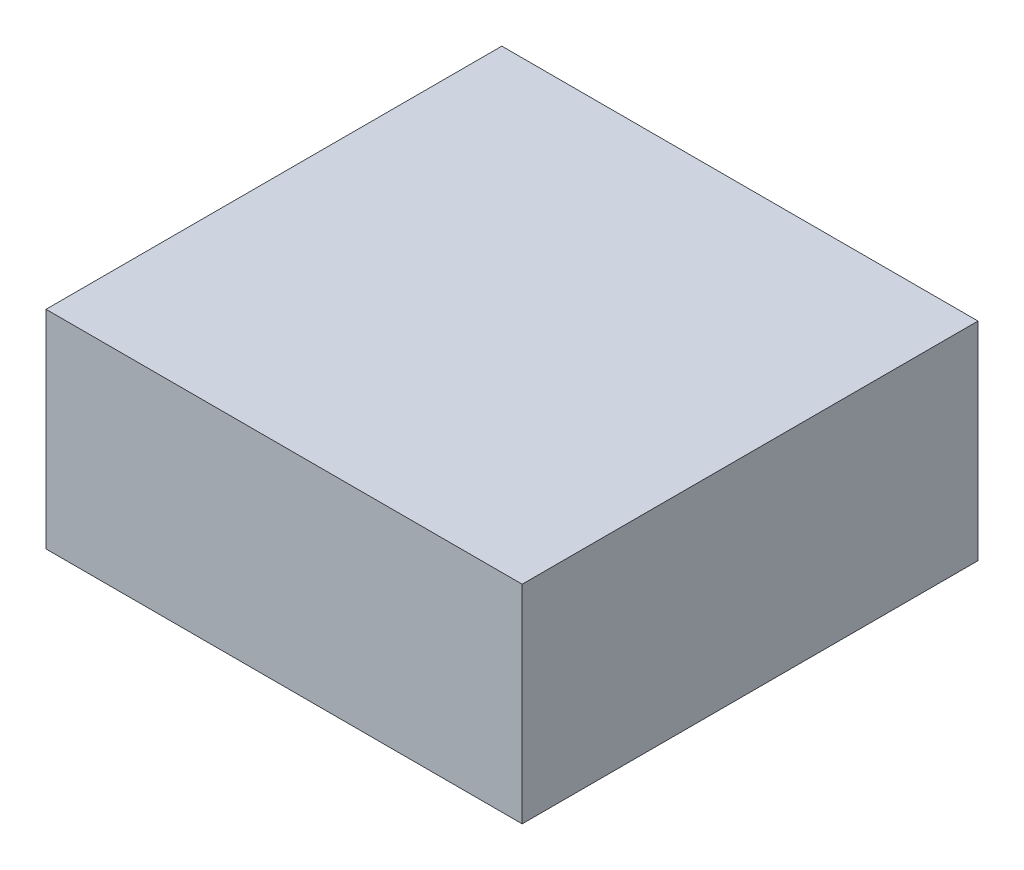
SolidWorks part; units mm, degrees
ref_plane "Front Plane" through (0, 0, 0) normal (0, 0, 1) x (1, 0, 0)
ref_plane "Top Plane" through (0, 0, 0) normal (0, 1, 0) x (1, 0, 0)
ref_plane "Right Plane" through (0, 0, 0) normal (1, 0, 0) x (0, 0, -1)
sketch "ｽｹｯﾁ1" plane through (0, 0, 0) normal (0, 0, 1) x (1, 0, 0)
  line L1 (-58.5, -25.5) -> (58.5, -25.5)
  line L2 (-58.5, -25.5) -> (-58.5, 25.5)
  line L3 (-58.5, 25.5) -> (58.5, 25.5)
  line L4 (58.5, -25.5) -> (58.5, 25.5)
  line L5 (-58.5, -25.5) -> (58.5, 25.5) construction
  line L6 (-58.5, 25.5) -> (58.5, -25.5) construction
  point P0 (0, 0)
  dimension "D1" = 117
  dimension "D2" = 51
extrude "ﾎﾞｽ - 押し出し1" add sketch "ｽｹｯﾁ1" along normal mid plane 112
